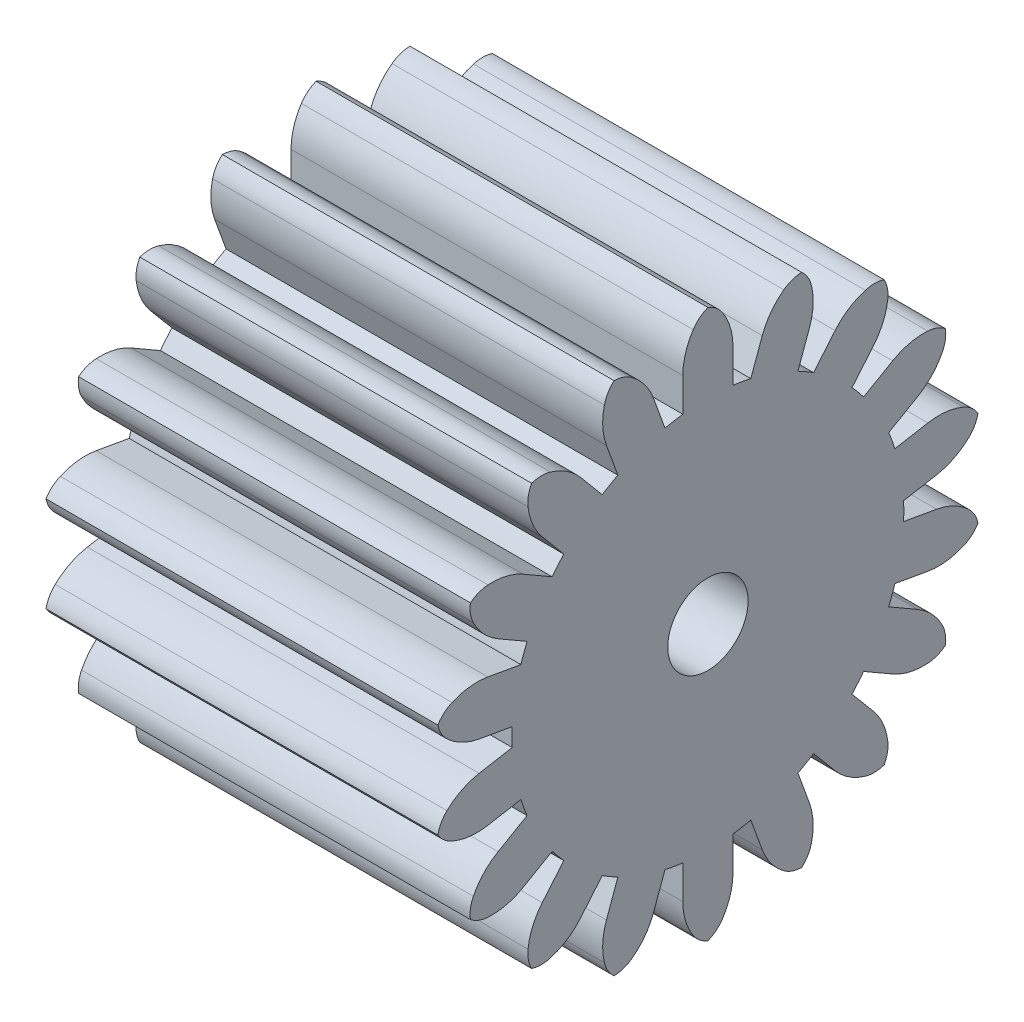
SolidWorks part; units mm, degrees
ref_plane "Front Plane" through (0, 0, 0) normal (0, 0, 1) x (1, 0, 0)
ref_plane "Top Plane" through (0, 0, 0) normal (0, 1, 0) x (1, 0, 0)
ref_plane "Right Plane" through (0, 0, 0) normal (1, 0, 0) x (0, 0, -1)
sketch "Sketch1" plane through (0, 0, 0) normal (1, 0, 0) x (0, 0, -1)
  line L0 (-0.64, 4.9589) -> (-0.64, 5.8144)
  line L1 (0, 7) -> (0, 5)
  line L2 (0, 55) -> (0, -55) construction
  line L3 (0.64, 4.9589) -> (0.64, 5.8144)
  line L4 (2.2974, 4.4409) -> (2.5901, 5.2449)
  line L5 (1.0946, 4.8787) -> (1.3872, 5.6827)
  line L6 (3.6778, 3.3873) -> (4.2277, 4.0427)
  line L7 (2.6972, 4.2101) -> (3.2472, 4.8655)
  line L8 (4.6145, 1.9252) -> (5.3554, 2.353)
  line L9 (3.9745, 3.0337) -> (4.7154, 3.4615)
  line L10 (4.9947, 0.2308) -> (5.8372, 0.3794)
  line L11 (4.7724, 1.4914) -> (5.615, 1.6399)
  line L12 (4.7724, -1.4914) -> (5.615, -1.6399)
  line L13 (4.9947, -0.2308) -> (5.8372, -0.3794)
  line L14 (3.9745, -3.0337) -> (4.7154, -3.4615)
  line L15 (4.6145, -1.9252) -> (5.3554, -2.353)
  line L16 (2.6972, -4.2101) -> (3.2472, -4.8655)
  line L17 (3.6778, -3.3873) -> (4.2277, -4.0427)
  line L18 (1.0946, -4.8787) -> (1.3872, -5.6827)
  line L19 (2.2974, -4.4409) -> (2.5901, -5.2449)
  line L20 (-0.64, -4.9589) -> (-0.64, -5.8144)
  line L21 (0.64, -4.9589) -> (0.64, -5.8144)
  line L22 (-2.2974, -4.4409) -> (-2.5901, -5.2449)
  line L23 (-1.0946, -4.8787) -> (-1.3872, -5.6827)
  line L24 (-3.6778, -3.3873) -> (-4.2277, -4.0427)
  line L25 (-2.6972, -4.2101) -> (-3.2472, -4.8655)
  line L26 (-4.6145, -1.9252) -> (-5.3554, -2.353)
  line L27 (-3.9745, -3.0337) -> (-4.7154, -3.4615)
  line L28 (-4.9947, -0.2308) -> (-5.8372, -0.3794)
  line L29 (-4.7724, -1.4914) -> (-5.615, -1.6399)
  line L30 (-4.7724, 1.4914) -> (-5.615, 1.6399)
  line L31 (-4.9947, 0.2308) -> (-5.8372, 0.3794)
  line L32 (-3.9745, 3.0337) -> (-4.7154, 3.4615)
  line L33 (-4.6145, 1.9252) -> (-5.3554, 2.353)
  line L34 (-2.6972, 4.2101) -> (-3.2472, 4.8655)
  line L35 (-3.6778, 3.3873) -> (-4.2277, 4.0427)
  line L36 (-1.0946, 4.8787) -> (-1.3872, 5.6827)
  line L37 (-2.2974, 4.4409) -> (-2.5901, 5.2449)
  circle A0 centre (0, 0) radius 1.025
  circle A1 centre (0, 0) radius 5
  arc A2 (-0.64, 5.8144) -> (-0.375, 6.6963) centre (0.96, 5.8144) cw
  arc A3 (-0.375, 6.6963) -> (0, 7) centre (0.2925, 6.2554) cw
  arc A4 (0.64, 5.8144) -> (0.375, 6.6963) centre (-0.96, 5.8144) ccw
  arc A5 (0.375, 6.6963) -> (0, 7) centre (-0.2925, 6.2554) ccw
  arc A6 (2.5901, 5.2449) -> (2.6427, 6.1643) centre (1.0865, 5.7921) ccw
  arc A7 (1.3872, 5.6827) -> (1.9379, 6.4208) centre (2.8908, 5.1354) cw
  arc A8 (1.9379, 6.4208) -> (2.3941, 6.5778) centre (2.4143, 5.7781) cw
  arc A9 (2.6427, 6.1643) -> (2.3941, 6.5778) centre (1.8646, 5.9782) ccw
  arc A10 (4.2277, 4.0427) -> (4.5916, 4.8887) centre (3.002, 5.0712) ccw
  arc A11 (3.2472, 4.8655) -> (4.0171, 5.3707) centre (4.4728, 3.837) cw
  arc A12 (4.0171, 5.3707) -> (4.4995, 5.3623) centre (4.245, 4.6039) cw
  arc A13 (4.5916, 4.8887) -> (4.4995, 5.3623) centre (3.7968, 4.9799) ccw
  arc A14 (5.3554, 2.353) -> (5.9867, 3.0234) centre (4.5554, 3.7386) ccw
  arc A15 (4.7154, 3.4615) -> (5.6117, 3.6729) centre (5.5154, 2.0758) cw
  arc A16 (5.6117, 3.6729) -> (6.0622, 3.5) centre (5.5636, 2.8744) cw
  arc A17 (5.9867, 3.0234) -> (6.0622, 3.5) centre (5.2711, 3.381) ccw
  arc A18 (5.8372, 0.3794) -> (6.6597, 0.7935) centre (5.5594, 1.9551) ccw
  arc A19 (5.615, 1.6399) -> (6.5295, 1.5321) centre (5.8928, 0.0643) cw
  arc A20 (6.5295, 1.5321) -> (6.8937, 1.2155) centre (6.2111, 0.7982) cw
  arc A21 (6.6597, 0.7935) -> (6.8937, 1.2155) centre (6.1096, 1.3743) ccw
  arc A22 (5.615, -1.6399) -> (6.5295, -1.5321) centre (5.8928, -0.0643) ccw
  arc A23 (5.8372, -0.3794) -> (6.6597, -0.7935) centre (5.5594, -1.9551) cw
  arc A24 (6.6597, -0.7935) -> (6.8937, -1.2155) centre (6.1096, -1.3743) cw
  arc A25 (6.5295, -1.5321) -> (6.8937, -1.2155) centre (6.2111, -0.7982) ccw
  arc A26 (4.7154, -3.4615) -> (5.6117, -3.6729) centre (5.5154, -2.0758) ccw
  arc A27 (5.3554, -2.353) -> (5.9867, -3.0234) centre (4.5554, -3.7386) cw
  arc A28 (5.9867, -3.0234) -> (6.0622, -3.5) centre (5.2711, -3.381) cw
  arc A29 (5.6117, -3.6729) -> (6.0622, -3.5) centre (5.5636, -2.8744) ccw
  arc A30 (3.2472, -4.8655) -> (4.0171, -5.3707) centre (4.4728, -3.837) ccw
  arc A31 (4.2277, -4.0427) -> (4.5916, -4.8887) centre (3.002, -5.0712) cw
  arc A32 (4.5916, -4.8887) -> (4.4995, -5.3623) centre (3.7968, -4.9799) cw
  arc A33 (4.0171, -5.3707) -> (4.4995, -5.3623) centre (4.245, -4.6039) ccw
  arc A34 (1.3872, -5.6827) -> (1.9379, -6.4208) centre (2.8908, -5.1354) ccw
  arc A35 (2.5901, -5.2449) -> (2.6427, -6.1643) centre (1.0865, -5.7921) cw
  arc A36 (2.6427, -6.1643) -> (2.3941, -6.5778) centre (1.8646, -5.9782) cw
  arc A37 (1.9379, -6.4208) -> (2.3941, -6.5778) centre (2.4143, -5.7781) ccw
  arc A38 (-0.64, -5.8144) -> (-0.375, -6.6963) centre (0.96, -5.8144) ccw
  arc A39 (0.64, -5.8144) -> (0.375, -6.6963) centre (-0.96, -5.8144) cw
  arc A40 (0.375, -6.6963) -> (0, -7) centre (-0.2925, -6.2554) cw
  arc A41 (-0.375, -6.6963) -> (0, -7) centre (0.2925, -6.2554) ccw
  arc A42 (-2.5901, -5.2449) -> (-2.6427, -6.1643) centre (-1.0865, -5.7921) ccw
  arc A43 (-1.3872, -5.6827) -> (-1.9379, -6.4208) centre (-2.8908, -5.1354) cw
  arc A44 (-1.9379, -6.4208) -> (-2.3941, -6.5778) centre (-2.4143, -5.7781) cw
  arc A45 (-2.6427, -6.1643) -> (-2.3941, -6.5778) centre (-1.8646, -5.9782) ccw
  arc A46 (-4.2277, -4.0427) -> (-4.5916, -4.8887) centre (-3.002, -5.0712) ccw
  arc A47 (-3.2472, -4.8655) -> (-4.0171, -5.3707) centre (-4.4728, -3.837) cw
  arc A48 (-4.0171, -5.3707) -> (-4.4995, -5.3623) centre (-4.245, -4.6039) cw
  arc A49 (-4.5916, -4.8887) -> (-4.4995, -5.3623) centre (-3.7968, -4.9799) ccw
  arc A50 (-5.3554, -2.353) -> (-5.9867, -3.0234) centre (-4.5554, -3.7386) ccw
  arc A51 (-4.7154, -3.4615) -> (-5.6117, -3.6729) centre (-5.5154, -2.0758) cw
  arc A52 (-5.6117, -3.6729) -> (-6.0622, -3.5) centre (-5.5636, -2.8744) cw
  arc A53 (-5.9867, -3.0234) -> (-6.0622, -3.5) centre (-5.2711, -3.381) ccw
  arc A54 (-5.8372, -0.3794) -> (-6.6597, -0.7935) centre (-5.5594, -1.9551) ccw
  arc A55 (-5.615, -1.6399) -> (-6.5295, -1.5321) centre (-5.8928, -0.0643) cw
  arc A56 (-6.5295, -1.5321) -> (-6.8937, -1.2155) centre (-6.2111, -0.7982) cw
  arc A57 (-6.6597, -0.7935) -> (-6.8937, -1.2155) centre (-6.1096, -1.3743) ccw
  arc A58 (-5.615, 1.6399) -> (-6.5295, 1.5321) centre (-5.8928, 0.0643) ccw
  arc A59 (-5.8372, 0.3794) -> (-6.6597, 0.7935) centre (-5.5594, 1.9551) cw
  arc A60 (-6.6597, 0.7935) -> (-6.8937, 1.2155) centre (-6.1096, 1.3743) cw
  arc A61 (-6.5295, 1.5321) -> (-6.8937, 1.2155) centre (-6.2111, 0.7982) ccw
  arc A62 (-4.7154, 3.4615) -> (-5.6117, 3.6729) centre (-5.5154, 2.0758) ccw
  arc A63 (-5.3554, 2.353) -> (-5.9867, 3.0234) centre (-4.5554, 3.7386) cw
  arc A64 (-5.9867, 3.0234) -> (-6.0622, 3.5) centre (-5.2711, 3.381) cw
  arc A65 (-5.6117, 3.6729) -> (-6.0622, 3.5) centre (-5.5636, 2.8744) ccw
  arc A66 (-3.2472, 4.8655) -> (-4.0171, 5.3707) centre (-4.4728, 3.837) ccw
  arc A67 (-4.2277, 4.0427) -> (-4.5916, 4.8887) centre (-3.002, 5.0712) cw
  arc A68 (-4.5916, 4.8887) -> (-4.4995, 5.3623) centre (-3.7968, 4.9799) cw
  arc A69 (-4.0171, 5.3707) -> (-4.4995, 5.3623) centre (-4.245, 4.6039) ccw
  arc A70 (-1.3872, 5.6827) -> (-1.9379, 6.4208) centre (-2.8908, 5.1354) ccw
  arc A71 (-2.5901, 5.2449) -> (-2.6427, 6.1643) centre (-1.0865, 5.7921) cw
  arc A72 (-2.6427, 6.1643) -> (-2.3941, 6.5778) centre (-1.8646, 5.9782) cw
  arc A73 (-1.9379, 6.4208) -> (-2.3941, 6.5778) centre (-2.4143, 5.7781) ccw
  point P318 (0, 0)
  dimension "D1" = 2.05
  dimension "D2" = 10
  dimension "D6" = 1.6
  dimension "D7" = 0.8
  dimension "D4" = 2
  dimension "D5" = 1.28
  dimension "D8" = 0.75
  dimension "D3" = 18
extrude "Boss-Extrude1" add sketch "Sketch1" along normal blind 10 contours A1 A0 | A66 A69 A68 A67 L35 A1 L34 | A70 A73 A72 A71 L37 A1 L36 | A6 A9 A8 A7 L5 A1 L4 | A10 A13 A12 A11 L7 A1 L6 | A14 A17 A16 A15 L9 A1 L8 | A18 A21 A20 A19 L11 A1 L10 | A22 A25 A24 A23 L13 A1 L12 | A26 A29 A28 A27 L15 A1 L14 | A30 A33 A32 A31 L17 A1 L16 | A34 A37 A36 A35 L19 A1 L18 | A38 A41 A40 A39 L21 A1 L20 | A42 A45 A44 A43 L23 A1 L22 | A46 A49 A48 A47 L25 A1 L24 | A50 A53 A52 A51 L27 A1 L26 | A54 A57 A56 A55 L29 A1 L28 | A58 A61 A60 A59 L31 A1 L30 | A62 A65 A64 A63 L33 A1 L32 | A3 A2 L0 A1 L1 | A4 A5 L1 A1 L3
